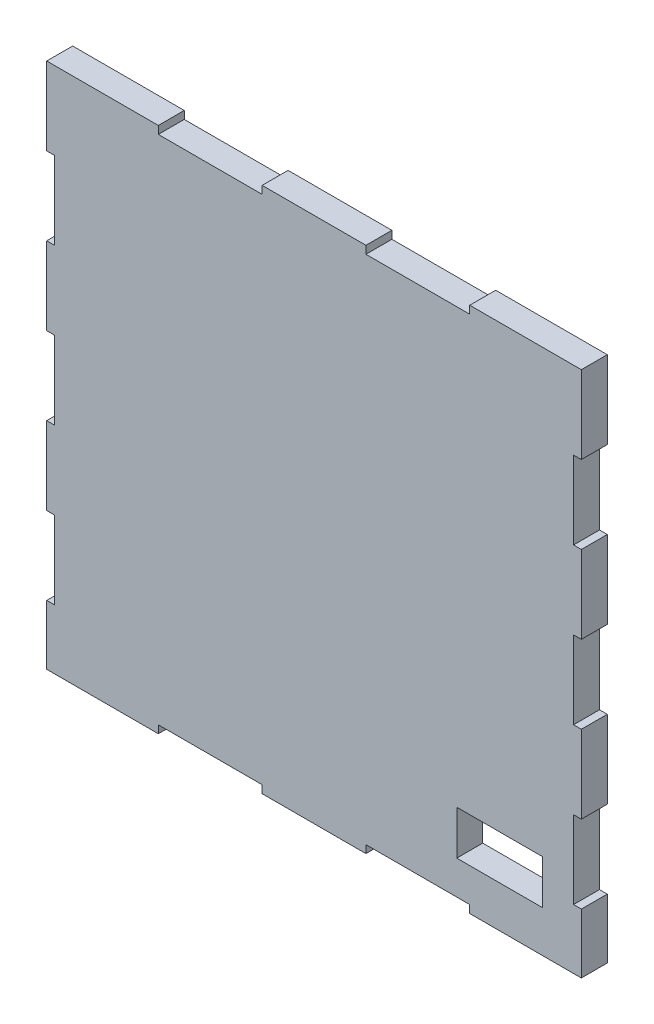
SolidWorks part; units mm, degrees
ref_plane "Front Plane" through (0, 0, 0) normal (0, 0, 1) x (1, 0, 0)
ref_plane "Top Plane" through (0, 0, 0) normal (0, 1, 0) x (1, 0, 0)
ref_plane "Right Plane" through (0, 0, 0) normal (1, 0, 0) x (0, 0, -1)
sketch "Sketch1" plane through (0, 0, 0) normal (0, 0, 1) x (1, 0, 0)
  line L0 (-103, -98.5) -> (-103, -101.5)
  line L1 (-103, 98.5) -> (103, 98.5)
  line L2 (-103, 98.5) -> (-103, -98.5)
  line L3 (-103, -98.5) -> (103, -98.5)
  line L4 (103, 98.5) -> (103, -98.5)
  line L5 (-103, 98.5) -> (103, -98.5) construction
  line L7 (-103, -101.5) -> (-60, -101.5)
  line L8 (-60, -101.5) -> (-60, -98.5)
  line L9 (-20, -98.5) -> (-20, -101.5)
  line L10 (-20, -101.5) -> (20, -101.5)
  line L11 (20, -101.5) -> (20, -98.5)
  line L12 (103, -98.5) -> (103, -101.5)
  line L13 (103, -101.5) -> (60, -101.5)
  line L14 (60, -101.5) -> (60, -98.5)
  line L15 (-103, -78.5) -> (-100, -78.5)
  line L16 (-100, -78.5) -> (-100, -48.5)
  line L17 (-100, -48.5) -> (-103, -48.5)
  line L18 (-103, -18.5) -> (-100, -18.5)
  line L19 (-100, -18.5) -> (-100, 11.5)
  line L20 (-100, 11.5) -> (-103, 11.5)
  line L21 (-103, 41.5) -> (-100, 41.5)
  line L22 (-100, 41.5) -> (-100, 71.5)
  line L23 (-100, 71.5) -> (-103, 71.5)
  line L24 (-103, 98.5) -> (-103, 101.5)
  line L25 (-103, 101.5) -> (-60, 101.5)
  line L26 (-60, 101.5) -> (-60, 98.5)
  line L27 (-20, 98.5) -> (-20, 101.5)
  line L28 (-20, 101.5) -> (20, 101.5)
  line L29 (20, 101.5) -> (20, 98.5)
  line L30 (60, 101.5) -> (60, 98.5)
  line L31 (60, 101.5) -> (103, 101.5)
  line L32 (103, 101.5) -> (103, 98.5)
  line L33 (100, 71.5) -> (103, 71.5)
  line L34 (100, 71.5) -> (100, 41.5)
  line L35 (88, -85.5) -> (88, -68.5)
  line L36 (55, -68.5) -> (88, -68.5)
  line L37 (55, -68.5) -> (55, -85.5)
  line L38 (100, 41.5) -> (103, 41.5)
  line L39 (100, 11.5) -> (103, 11.5)
  line L40 (100, 11.5) -> (100, -18.5)
  line L41 (100, -18.5) -> (103, -18.5)
  line L42 (100, -48.5) -> (103, -48.5)
  line L43 (100, -48.5) -> (100, -78.5)
  line L44 (100, -78.5) -> (103, -78.5)
  line L45 (55, -85.5) -> (88, -85.5)
  point P0 (0, 0)
  dimension "D1" = 206
  dimension "D2" = 197
  dimension "D3" = 43
  dimension "D4" = 40
  dimension "D5" = 40
  dimension "D6" = 40
  dimension "D7" = 3
  dimension "D8" = 3
  dimension "D9" = 30
  dimension "D10" = 30
  dimension "D11" = 30
  dimension "D12" = 30
  dimension "D13" = 30
  dimension "D14" = 30
  dimension "D15" = 43
  dimension "D16" = 40
  dimension "D17" = 40
  dimension "D18" = 40
  dimension "D19" = 3
  dimension "D20" = 15
  dimension "D21" = 17
  dimension "D22" = 33
  dimension "D23" = 30
  dimension "D24" = 30
  dimension "D25" = 30
  dimension "D26" = 30
  dimension "D27" = 30
  dimension "D34" = 170
  dimension "D35" = 30
extrude "Boss-Extrude1" add sketch "Sketch1" along normal blind 10 contours L29 L28 L27 L1 | L26 L25 L24 L1 | L32 L31 L30 L1 | L14 L13 L12 L3 | L10 L11 L3 L9 | L7 L8 L3 L0 | L1 L5 L36 L35 L4 L44 L43 L42 L41 L40 L39 L38 L34 L33 | L5 L2 L23 L22 L21 L20 L19 L18 L17 L16 L15 L3 L35 L45 L37 L36
